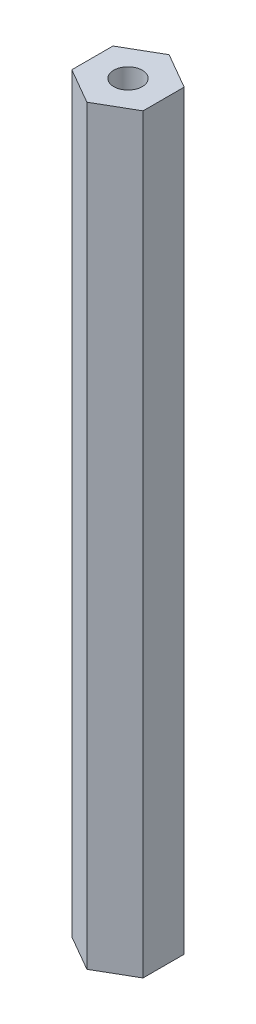
SolidWorks part; units mm, degrees
ref_plane "Front Plane" through (0, 0, 0) normal (0, 0, 1) x (1, 0, 0)
ref_plane "Top Plane" through (0, 0, 0) normal (0, 1, 0) x (1, 0, 0)
ref_plane "Right Plane" through (0, 0, 0) normal (1, 0, 0) x (0, 0, -1)
sketch "Sketch1" plane through (0, 0, 0) normal (0, 1, 0) x (1, 0, 0)
  line L1 (0, 4.1061) -> (-3.556, 2.0531)
  line L2 (-3.556, 2.0531) -> (-3.556, -2.0531)
  line L3 (-3.556, -2.0531) -> (0, -4.1061)
  line L4 (0, -4.1061) -> (3.556, -2.0531)
  line L5 (3.556, -2.0531) -> (3.556, 2.0531)
  line L6 (3.556, 2.0531) -> (0, 4.1061)
  circle A0 centre (0, 0) radius 1.425
  circle A1 centre (-46.75, -148.5) radius 1.425 construction
  circle A2 centre (0, 0) radius 3.556 construction
  circle A3 centre (-32.25, -86.65) radius 3.556 construction
  point P14 (0, 0)
extrude "Boss-Extrude1" add sketch "Sketch1" along normal blind 75
